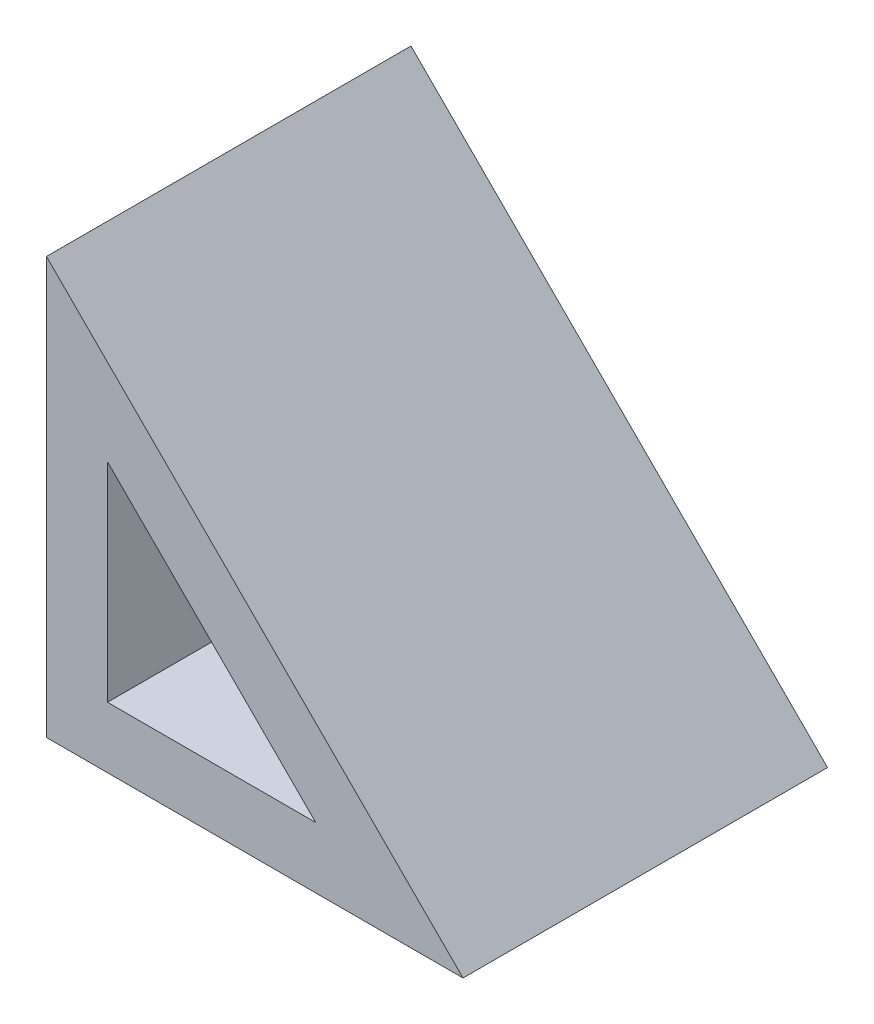
SolidWorks part; units mm, degrees
ref_plane "Front Plane" through (0, 0, 0) normal (0, 0, 1) x (1, 0, 0)
ref_plane "Top Plane" through (0, 0, 0) normal (0, 1, 0) x (1, 0, 0)
ref_plane "Right Plane" through (0, 0, 0) normal (1, 0, 0) x (0, 0, -1)
sketch "Sketch1" plane through (0, 0, 0) normal (0, 0, 1) x (1, 0, 0)
  line L0 (0, 25.4) -> (25.4, 0)
  line L1 (0, 0) -> (25.4, 0)
  line L2 (0, 0) -> (0, 25.4)
  dimension "D1" = 25.4
extrude "Boss-Extrude1" add sketch "Sketch1" along normal blind 22.225
sketch "Sketch2" plane through (0, 0, 22.225) normal (0, 0, 1) x (1, 0, 0)
  line L0 (3.7197, 16.4197) -> (16.4197, 3.7197)
  line L1 (3.7197, 3.7197) -> (16.4197, 3.7197)
  line L2 (3.7197, 3.7197) -> (3.7197, 16.4197)
  line L3 (0, 25.4) -> (0, 0) construction
  line L5 (3.7197, 10.0697) -> (0, 10.0697) construction
  line L6 (10.0697, 3.7197) -> (10.0697, 0) construction
  line L7 (0, 0) -> (25.4, 0) construction
  line L8 (10.0697, 10.0697) -> (12.7, 12.7) construction
  line L9 (25.4, 0) -> (0, 25.4) construction
  point P10 (3.7197, 10.0697)
  dimension "D1" = 12.7
  dimension "D2" = 3.7197
extrude "Cut-Extrude1" cut sketch "Sketch2" against normal through all
